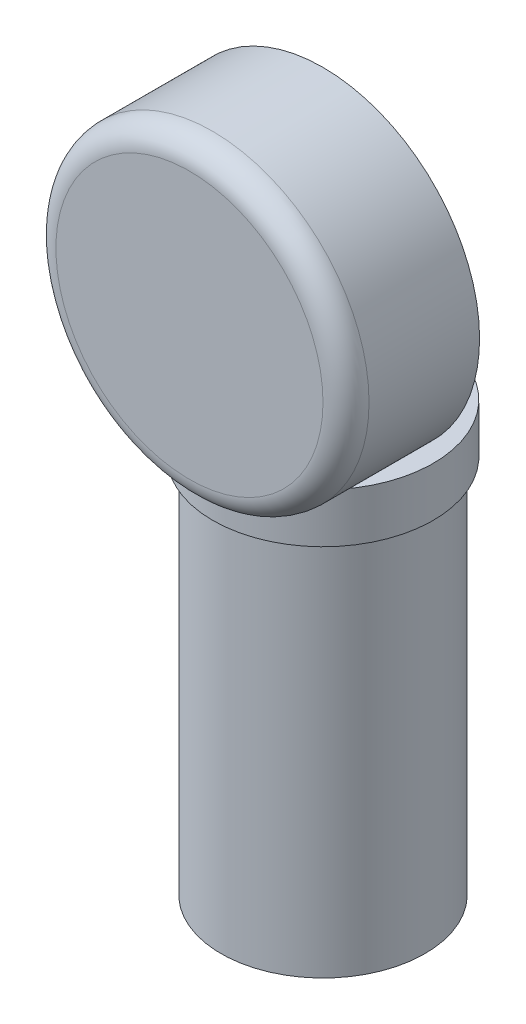
SolidWorks part; units mm, degrees
ref_plane "Front Plane" through (0, 0, 0) normal (0, 0, 1) x (1, 0, 0)
ref_plane "Top Plane" through (0, 0, 0) normal (0, 1, 0) x (1, 0, 0)
ref_plane "Right Plane" through (0, 0, 0) normal (1, 0, 0) x (0, 0, -1)
sketch "Sketch1" plane through (0, 0, 0) normal (0, 0, 1) x (1, 0, 0)
  circle A0 centre (-6.2728, -26.3144) radius 8.636
extrude "Extrude1" add sketch "Sketch1" along normal blind 7.366
fillet "Fillet1" radius 1.27 1 edges at (2.3632, -26.3144, 7.366)
sketch "Sketch2" plane through (0, 0, 0) normal (0, 0, 1) x (1, 0, 0)
  line L0 (-6.2728, -33.5574) -> (-6.2728, -36.2819)
  line L1 (-6.2728, -36.2819) -> (-12.353, -36.2819)
  line L2 (-12.353, -36.2819) -> (-12.353, -33.5574)
  line L3 (-12.353, -33.5574) -> (-6.2728, -33.5574)
revolve "Revolve1" add sketch "Sketch2" angle 360 about L0
sketch "Sketch3" plane through (0, -36.2819, 0) normal (0, -1, 0) x (1, 0, 0)
  circle A0 centre (-6.2728, 0) radius 5.6268
extrude "Extrude2" add sketch "Sketch3" along normal blind 20.9229
